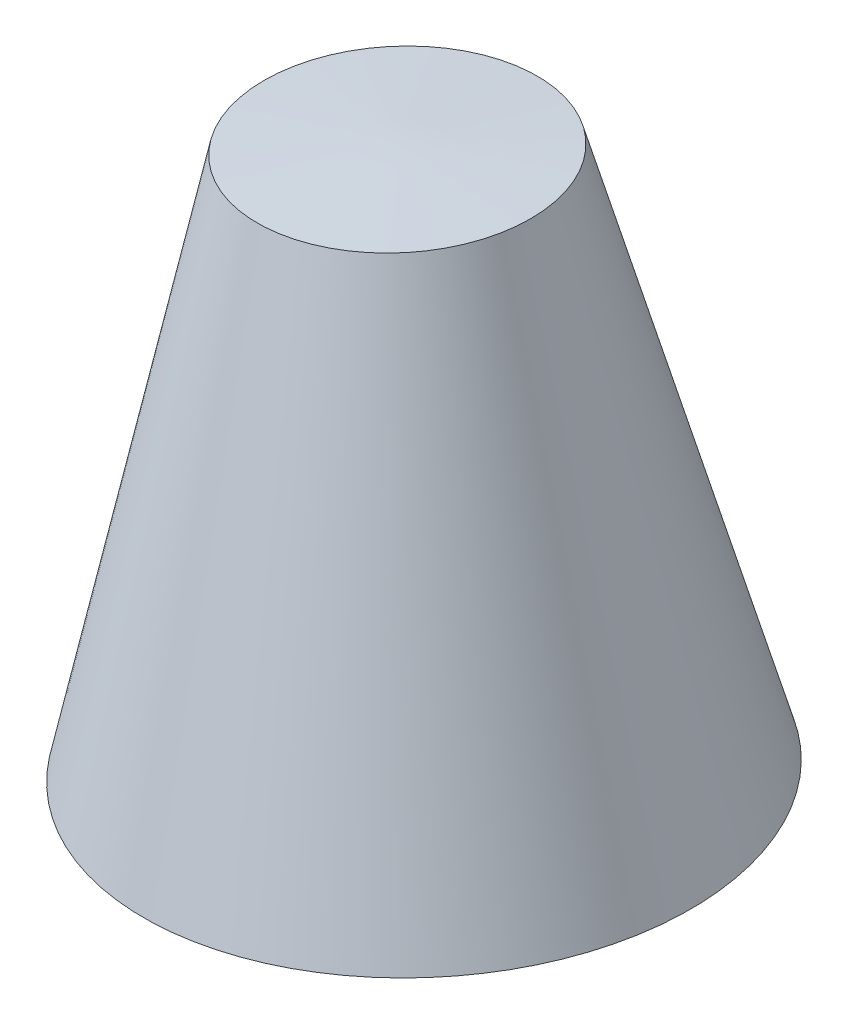
SolidWorks part; units mm, degrees
material "BUTYL"
ref_plane "Front Plane" through (0, 0, 0) normal (0, 0, 1) x (1, 0, 0)
ref_plane "Top Plane" through (0, 0, 0) normal (0, 1, 0) x (1, 0, 0)
ref_plane "Right Plane" through (0, 0, 0) normal (1, 0, 0) x (0, 0, -1)
sketch "Sketch1" plane through (0, 0, 0) normal (0, 0, 1) x (1, 0, 0)
  line L0 (-24.2303, 31.9153) -> (-22.9645, 6.9617)
  line L1 (-22.9645, 6.9617) -> (-10.4466, 7.5967)
  line L2 (-10.4466, 7.5967) -> (-17.9552, 31.9153)
  line L3 (-17.9552, 31.9153) -> (-24.2303, 31.9153)
revolve "Revolve1" add sketch "Sketch1" angle 360 about L0
scale "Scale1" scale about centroid uniform scaling yes scale factor 3
